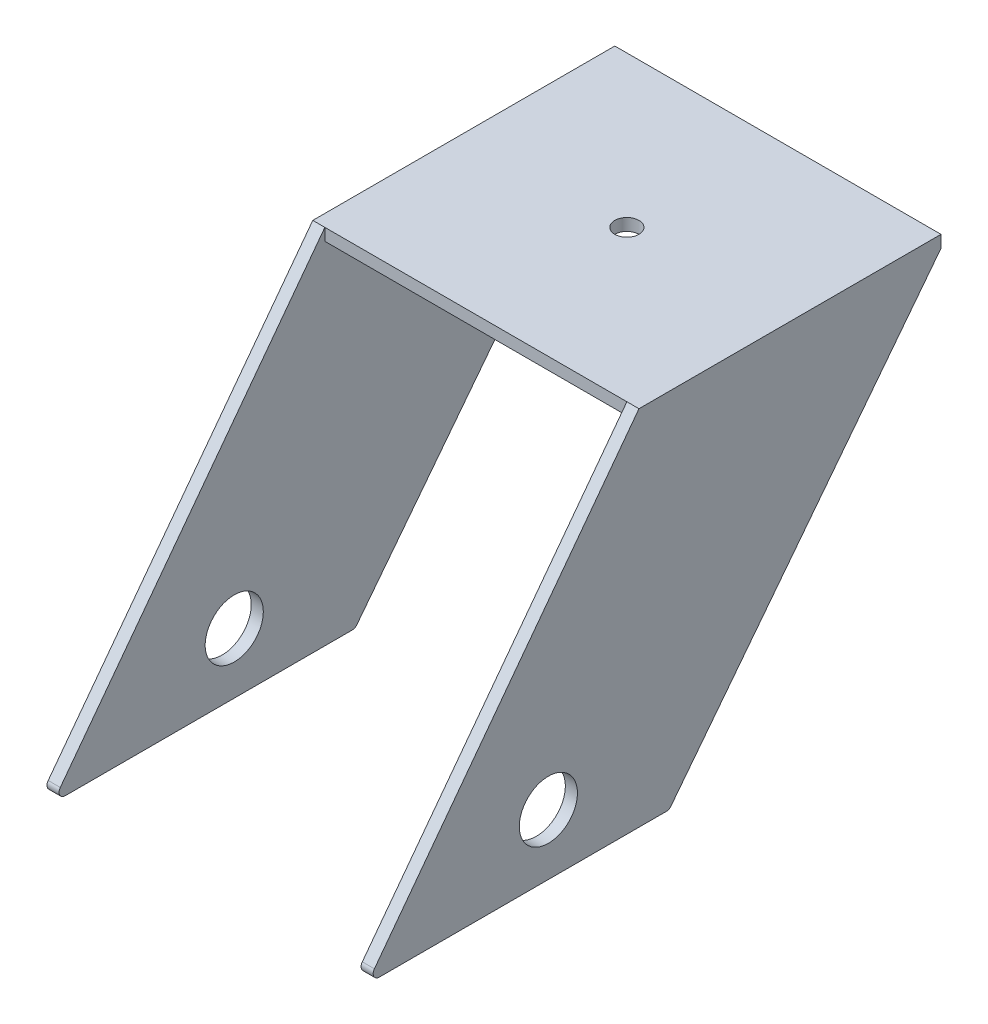
SolidWorks part; units mm, degrees
ref_plane "Front Plane" through (0, 0, 0) normal (0, 0, 1) x (1, 0, 0)
ref_plane "Top Plane" through (0, 0, 0) normal (0, 1, 0) x (1, 0, 0)
ref_plane "Right Plane" through (0, 0, 0) normal (1, 0, 0) x (0, 0, -1)
sketch "Sketch2" plane through (0, 0, 0) normal (0, 1, 0) x (1, 0, 0)
  line L1 (-25, 25) -> (25, 25)
  line L2 (-25, 25) -> (-25, -25)
  line L3 (-25, -25) -> (25, -25)
  line L4 (25, 25) -> (25, -25)
  circle A0 centre (0, 0) radius 2
  dimension "D5" = 4
  dimension "D1" = 50
  dimension "D2" = 50
  dimension "D3" = 25
  dimension "D4" = 25
extrude "Boss-Extrude1" add sketch "Sketch2" along normal blind 2
sketch "Sketch3" plane through (25, 0, 0) normal (1, 0, 0) x (0, 0, -1)
  line L0 (-25, 2) -> (-70, -58)
  line L1 (-70, -58) -> (-20, -58)
  line L2 (-20, -58) -> (25, 0)
  line L3 (-25, 2) -> (25, 2) construction
  line L4 (25, 0) -> (25, 2)
  line L5 (25, 2) -> (-25, 2)
  circle A0 centre (-40, -48) radius 4.8128
  dimension "D1" = 50
  dimension "D2" = 40
  dimension "D3" = 50
  dimension "D5" = 10
  dimension "D4" = 30
sketch "Sketch4" plane through (-25, 0, 0) normal (-1, 0, 0) x (0, 0, 1)
  line L0 (25, 2) -> (-25, 2)
  line L1 (-25, 2) -> (-25, 0) construction
  line L2 (-25, 2) -> (25, 2) construction
  line L3 (-25, 0.0263) -> (-25, 2)
  line L6 (-25, 2.0263) -> (-25, -47.9737) construction
  line L8 (20, -58) -> (-25, 0.0263)
  line L9 (70, -58) -> (20, -58)
  line L10 (25, 2) -> (70, -58)
  circle A1 centre (40, -48) radius 4.8128
  circle A2 centre (40, -48) radius 4.8128 construction
extrude "Boss-Extrude2" add sketch "Sketch4" along normal blind 2
extrude "Boss-Extrude3" add sketch "Sketch3" along normal blind 2
fillet "Fillet1" radius 1 2 edges at (26, -58, 20) (-26, -58, 20)
fillet "Fillet2" radius 1 2 edges at (26, -58, 70) (-26, -58, 70)
equation "\"d\"= 40"
equation "\"D2@Sketch3\"=\"d\""
